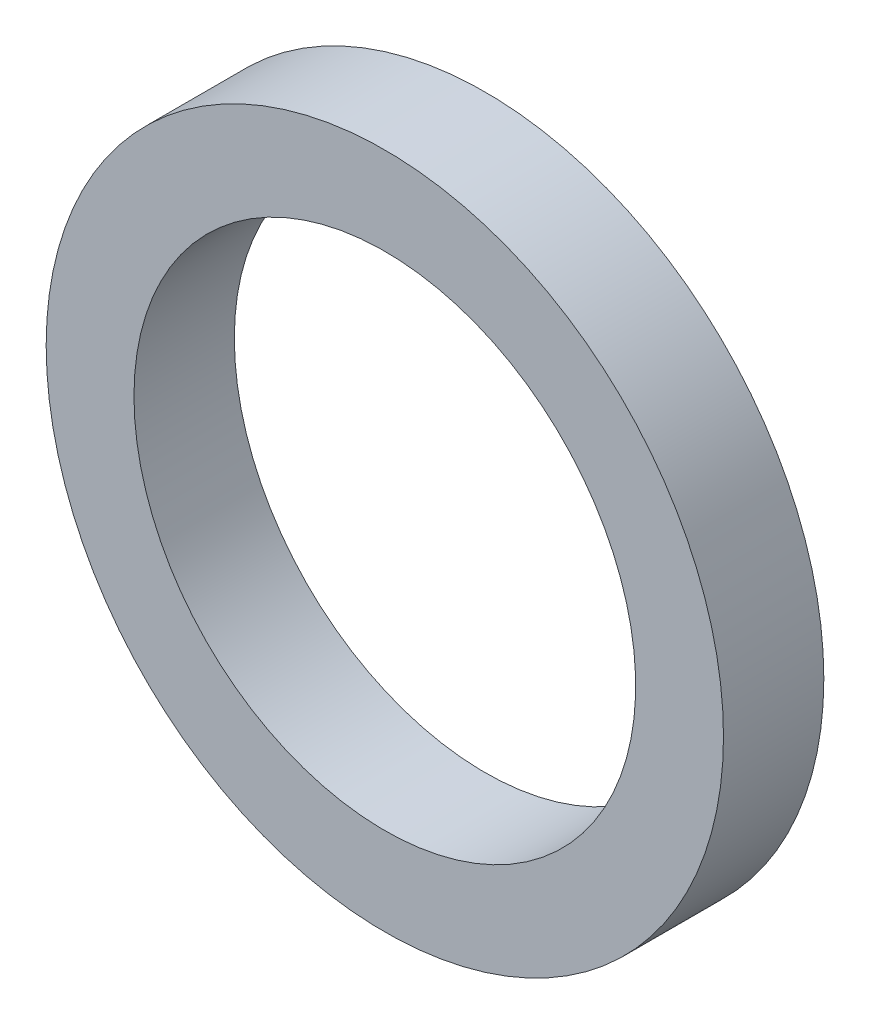
SolidWorks part; units mm, degrees
ref_plane "正面" through (0, 0, 0) normal (0, 0, 1) x (1, 0, 0)
ref_plane "平面" through (0, 0, 0) normal (0, 1, 0) x (1, 0, 0)
ref_plane "右側面" through (0, 0, 0) normal (1, 0, 0) x (0, 0, -1)
sketch "ｽｹｯﾁ1" plane through (0, 0, 0) normal (0, 0, 1) x (1, 0, 0)
  circle A0 centre (0, 0) radius 13.5
  dimension "D1" = 27
extrude "ﾎﾞｽ - 押し出し1" add sketch "ｽｹｯﾁ1" along normal blind 4
sketch "ｽｹｯﾁ2" plane through (0, 0, 0) normal (0, 0, -1) x (-1, 0, 0)
  circle A0 centre (0, 0) radius 10
  dimension "D1" = 20
extrude "ｶｯﾄ - 押し出し1" cut sketch "ｽｹｯﾁ2" against normal through all
